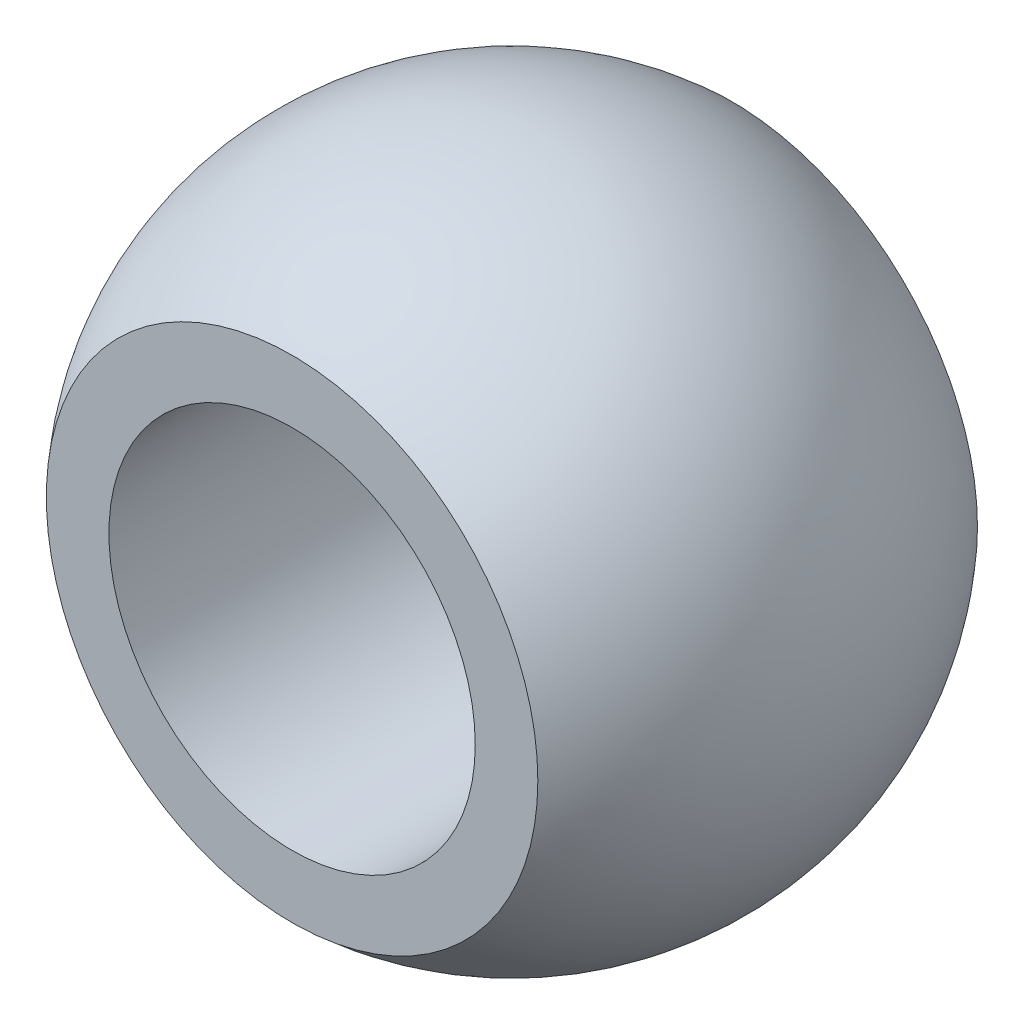
SolidWorks part; units mm, degrees
material "Alloy Steel"
ref_plane "Front Plane" through (0, 0, 0) normal (0, 0, 1) x (1, 0, 0)
ref_plane "Top Plane" through (0, 0, 0) normal (0, 1, 0) x (1, 0, 0)
ref_plane "Right Plane" through (0, 0, 0) normal (1, 0, 0) x (0, 0, -1)
sketch "Sketch1" plane through (0, 0, 0) normal (0, 0, 1) x (1, 0, 0)
  line L0 (0, -14.2875) -> (0, 14.2875) construction
  line L1 (0, 14.2875) -> (0, -14.2875)
  arc A0 (0, 14.2875) -> (0, -14.2875) centre (0, 0) cw
  dimension "D1" = 14.2875
revolve "Revolve1" add sketch "Sketch1" angle 360 about L0
sketch "Sketch2" plane through (0, 0, 0) normal (0, 0, 1) x (1, 0, 0)
  circle A0 centre (0, 0) radius 7.9375
  dimension "D1" = 15.875
extrude "Extrude1" cut sketch "Sketch2" against normal mid plane 50.8
ref_plane "Plane1" through (0, 0, 9.525) normal (0, 0, 1) x (1, 0, 0)
sketch "Sketch3" plane through (0, 0, 9.525) normal (0, 0, 1) x (1, 0, 0)
  circle A0 centre (0, 0) radius 14.2875 construction
  circle A1 centre (0, 0) radius 14.2875
extrude "Extrude2" cut sketch "Sketch3" along normal up to next
mirror "Mirror1" about plane through (0, 0, 0) normal (0, 0, 1) of "Extrude2"
